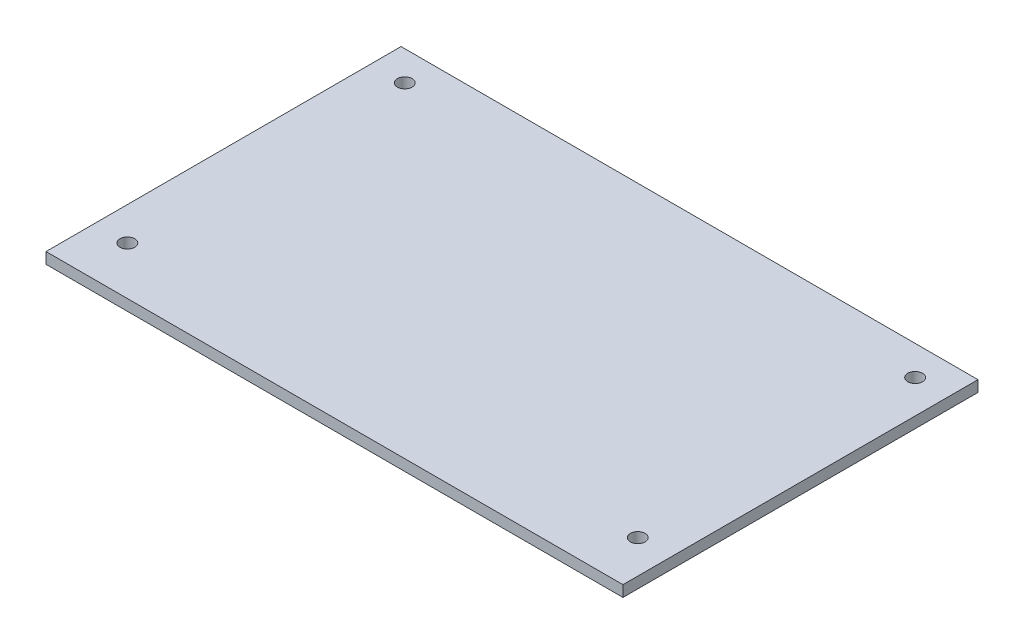
SolidWorks part; units mm, degrees
ref_plane "Front Plane" through (0, 0, 0) normal (0, 0, 1) x (1, 0, 0)
ref_plane "Top Plane" through (0, 0, 0) normal (0, 1, 0) x (1, 0, 0)
ref_plane "Right Plane" through (0, 0, 0) normal (1, 0, 0) x (0, 0, -1)
sketch "Sketch1" plane through (0, 0, 0) normal (0, 1, 0) x (1, 0, 0)
  line L1 (39, -24) -> (-39, -24)
  line L2 (39, -24) -> (39, 24)
  line L3 (39, 24) -> (-39, 24)
  line L4 (-39, -24) -> (-39, 24)
  line L5 (39, -24) -> (-39, 24) construction
  line L6 (39, 24) -> (-39, -24) construction
  point P0 (0, 0)
  dimension "D1" = 48
  dimension "D2" = 78
extrude "Boss-Extrude1" add sketch "Sketch1" along normal blind 1.5
sketch "Sketch2" plane through (0, 1.5, 0) normal (0, 1, 0) x (1, 0, 0)
  circle A0 centre (-34.5, 20) radius 1
  circle A1 centre (34.5, 20) radius 1
  circle A2 centre (-34.5, -17.5) radius 1
  circle A3 centre (34.5, -17.5) radius 1
extrude "Cut-Extrude1" cut sketch "Sketch2" against normal blind 10
